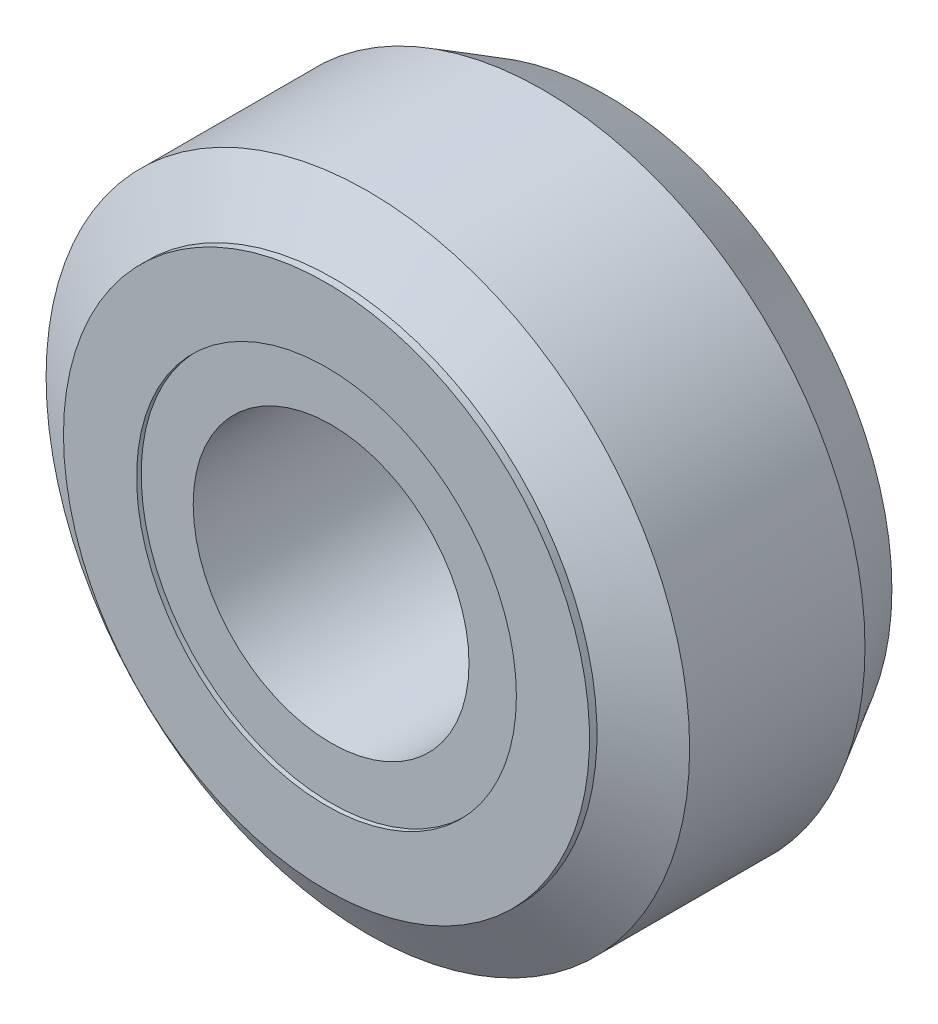
SolidWorks part; units mm, degrees
material "Acero aleado"
ref_plane "Alzado" through (0, 0, 0) normal (0, 0, 1) x (1, 0, 0)
ref_plane "Planta" through (0, 0, 0) normal (0, 1, 0) x (1, 0, 0)
ref_plane "Vista lateral" through (0, 0, 0) normal (1, 0, 0) x (0, 0, -1)
sketch "Croquis1" plane through (0, 0, 0) normal (0, 0, 1) x (1, 0, 0)
  circle A0 centre (0, 0) radius 3.5
  circle A1 centre (0, 0) radius 1.5
  dimension "D1" = 3
  dimension "D2" = 7
extrude "Saliente-Extruir1" add sketch "Croquis1" along normal mid plane 3
chamfer "Chaflán1" distance 0.4 angle 60 2 edges at (3.5, 0, -1.5) (3.5, 0, 1.5)
sketch "Croquis2" plane through (0, 0, 0) normal (0, 0, -1) x (-1, 0, 0)
  circle A0 centre (0, 0) radius 2.8609
  circle A1 centre (0, 0) radius 2.0655
extrude "Saliente-Extruir2" add sketch "Croquis2" along normal mid plane 3.1
